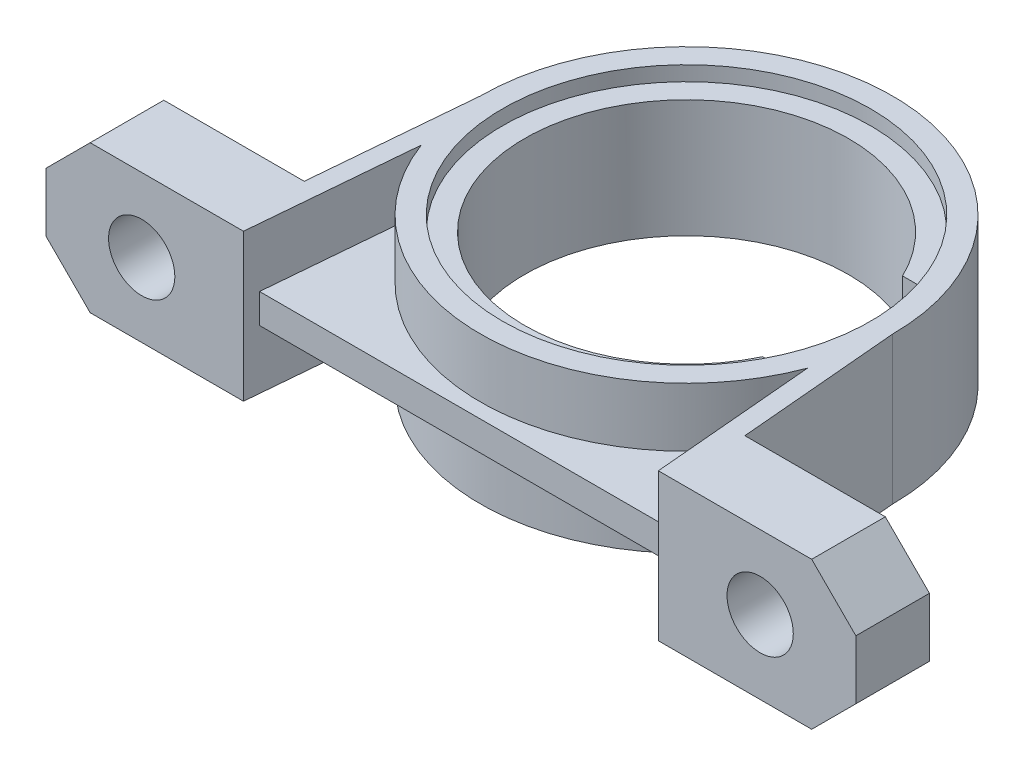
SolidWorks part; units mm, degrees
ref_plane "Front Plane" through (0, 0, 0) normal (0, 0, 1) x (1, 0, 0)
ref_plane "Top Plane" through (0, 0, 0) normal (0, 1, 0) x (1, 0, 0)
ref_plane "Right Plane" through (0, 0, 0) normal (1, 0, 0) x (0, 0, -1)
sketch "Esquisse2" plane through (0, 0, 0) normal (0, 1, 0) x (1, 0, 0)
  line L0 (0, 0) -> (0, 16) construction
  line L1 (14.0875, 0) -> (27.5, 0)
  line L2 (-14.0875, 0) -> (-27.5, 0)
  line L3 (-27.5, 0) -> (-27.5, 5)
  line L4 (27.5, 0) -> (27.5, 5)
  line L5 (-14, 16) -> (-14.9624, 5)
  line L6 (-14, 16) -> (-14, 6.1125) construction
  line L7 (-27.5, 5) -> (-14.9624, 5)
  line L8 (14, 16) -> (14.9624, 5)
  line L9 (14.9624, 5) -> (27.5, 5)
  line L10 (14, 16) -> (14, 4.0962) construction
  line L11 (-14, 1) -> (14, 1)
  line L12 (14, 1) -> (14.0875, 0)
  line L13 (-14, 1) -> (-14.0875, 0)
  arc A0 (14, 16) -> (-14, 16) centre (0, 16) ccw
  point P15 (0, 1)
  dimension "D2" = 28
  dimension "D1" = 16
  dimension "D3" = 27.5
  dimension "D4" = 27.5
  dimension "D5" = 5
  dimension "D6" = 5
  dimension "D7" = 5
  dimension "D8" = 5
  dimension "D9" = 28
  dimension "D10" = 1
extrude "Boss.-Extru.1" add sketch "Esquisse2" along normal blind 10
sketch "Esquisse3" plane through (0, 0, 0) normal (0, 0, 1) x (1, 0, 0)
  line L0 (0, 0) -> (0, 10) construction
  line L1 (-21, 5) -> (21, 5) construction
  line L2 (-14, 10) -> (14, 10) construction
  line L3 (-27.5, 3) -> (-24.5, 0)
  line L4 (-27.5, 10) -> (-27.5, 0) construction
  line L5 (16.5, 0) -> (-16.5, 0) construction
  line L6 (-27.5, 10) -> (-27.5, 7)
  line L7 (-27.5, 7) -> (-24.5, 10)
  line L8 (27.5, 7) -> (24.5, 10)
  line L9 (27.5, 3) -> (24.5, 0)
  line L10 (-27.5, 10) -> (-14.0875, 10) construction
  line L11 (-27.5, 10) -> (-24.5, 10)
  line L12 (-27.5, 0) -> (-14.0875, 0) construction
  line L13 (-27.5, 0) -> (-24.5, 0)
  line L14 (-27.5, 3) -> (-27.5, 0)
  line L15 (27.5, 10) -> (27.5, 0) construction
  line L16 (27.5, 10) -> (27.5, 7)
  line L17 (14.0875, 10) -> (27.5, 10) construction
  line L18 (24.5, 10) -> (27.5, 10)
  line L19 (14.0875, 0) -> (27.5, 0) construction
  line L20 (24.5, 0) -> (27.5, 0)
  line L21 (27.5, 3) -> (27.5, 0)
  circle A0 centre (-21, 5) radius 2.25
  circle A1 centre (21, 5) radius 2.25
  point P10 (0, 5)
  point P11 (0, 5)
  dimension "D2" = 4.5
  dimension "D1" = 42
  dimension "D3" = 45
  dimension "D4" = 3
extrude "Enlèv. mat.-Extru.1" cut sketch "Esquisse3" against normal up to surface (5 mm away) up to face at (-21.2312, 5, -5)
sketch "Esquisse5" plane through (0, 10, 0) normal (0, 1, 0) x (1, 0, 0)
  line L0 (0, 0) -> (0, 16) construction
  circle A0 centre (0, 16) radius 11
  dimension "D2" = 22
  dimension "D1" = 16
extrude "Enlèv. mat.-Extru.2" cut sketch "Esquisse5" against normal blind 10
sketch "Esquisse6" plane through (0, 10, 0) normal (0, 1, 0) x (1, 0, 0)
  circle A0 centre (0, 16) radius 12.5
  dimension "D2" = 25
extrude "Enlèv. mat.-Extru.3" cut sketch "Esquisse6" against normal blind 1
sketch "Esquisse7" plane through (0, 0, 0) normal (0, -1, 0) x (1, 0, 0)
  circle A0 centre (0, -16) radius 12.5
  dimension "D2" = 25
extrude "Enlèv. mat.-Extru.4" cut sketch "Esquisse7" against normal blind 1
sketch "Esquisse8" plane through (0, 9, 0) normal (0, 1, 0) x (1, 0, 0)
  line L0 (0, 0) -> (0, 16) construction
  line L4 (11.5623, 20.75) -> (9.9216, 20.75)
  line L5 (9.9216, 11.25) -> (11.5623, 11.25)
  arc A3 (11.5623, 20.75) -> (11.5623, 11.25) centre (0, 16) cw
  arc A4 (9.9216, 20.75) -> (9.9216, 11.25) centre (0, 16) cw
  dimension "D3" = 16
extrude "Enlèv. mat.-Extru.5" cut sketch "Esquisse8" against normal blind 5
sketch "Esquisse9" plane through (0, 10, 0) normal (0, 1, 0) x (1, 0, 0)
  line L0 (14, 1) -> (13.116, 11.1041)
  line L1 (-14, 1) -> (-13.116, 11.1041)
  line L11 (14.0875, 0) -> (27.5, 0)
  line L12 (27.5, 0) -> (27.5, 5)
  line L13 (27.5, 5) -> (14.9624, 5)
  line L14 (14.9624, 5) -> (14, 16)
  line L15 (-14, 16) -> (-14.9624, 5)
  line L16 (-14.9624, 5) -> (-27.5, 5)
  line L17 (-27.5, 5) -> (-27.5, 0)
  line L18 (-27.5, 0) -> (-14.0875, 0)
  line L19 (-14.0875, 0) -> (-14, 1)
  line L20 (-14, 1) -> (14, 1)
  line L21 (14, 1) -> (14.0875, 0)
  line L31 (-14, 1) -> (14, 1)
  arc A1 (14, 16) -> (-14, 16) centre (0, 16) ccw
  arc A3 (-13.116, 11.1041) -> (13.116, 11.1041) centre (0, 16) ccw
  dimension "D3" = 28
  dimension "D1" = 0
extrude "Enlèv. mat.-Extru.6" cut sketch "Esquisse9" against normal blind 4
sketch "Esquisse10" plane through (0, 0, 0) normal (0, -1, 0) x (1, 0, 0)
  line L3 (13.116, -11.1041) -> (14, -1)
  line L4 (-14, -1) -> (-13.116, -11.1041)
  line L5 (14, -1) -> (-14, -1)
  line L6 (13.116, -11.1041) -> (14, -1)
  line L7 (-14, -1) -> (-13.116, -11.1041)
  line L8 (14, -1) -> (-14, -1)
  arc A1 (13.116, -11.1041) -> (-13.116, -11.1041) centre (0, -16) ccw
  arc A2 (13.116, -11.1041) -> (-13.116, -11.1041) centre (0, -16) ccw
  dimension "D1" = 0
extrude "Enlèv. mat.-Extru.7" cut sketch "Esquisse10" against normal blind 4
